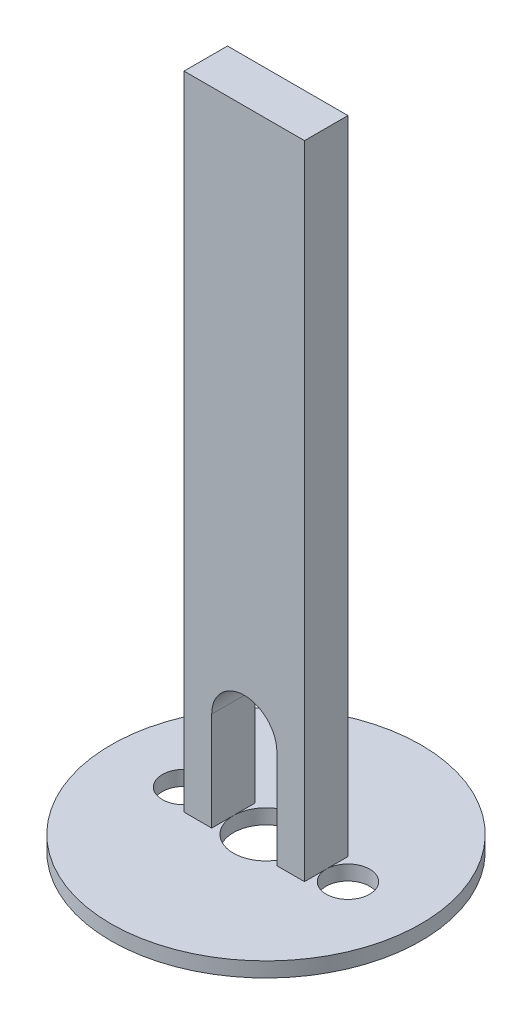
SolidWorks part; units mm, degrees
ref_plane "Front Plane" through (0, 0, 0) normal (0, 0, 1) x (1, 0, 0)
ref_plane "Top Plane" through (0, 0, 0) normal (0, 1, 0) x (1, 0, 0)
ref_plane "Right Plane" through (0, 0, 0) normal (1, 0, 0) x (0, 0, -1)
sketch "Sketch1" plane through (0, 0, 0) normal (0, 1, 0) x (1, 0, 0)
  line L0 (0, 45.1084) -> (0, -45.1084) construction
  line L1 (-87.8036, 0) -> (119.361, 0) construction
  circle A0 centre (0, 0) radius 15.7
  circle A1 centre (0, 0) radius 3.3
  circle A2 centre (-8.3, 0) radius 2.2
  circle A3 centre (8.3, 0) radius 2.2
  point P12 (0, 0)
  dimension "D1" = 31.4
  dimension "D2" = 6.6
  dimension "D3" = 4.4
  dimension "D5" = 4.4
  dimension "D4" = 8.3
  dimension "D6" = 8.3
extrude "Boss-Extrude1" add sketch "Sketch1" along normal blind 1.5
sketch "Sketch2" plane through (0, 1.5, 0) normal (0, 1, 0) x (1, 0, 0)
  line L0 (-23.3183, 0) -> (31.4321, 0) construction
  line L2 (-6.1, -2.2) -> (6.1, -2.2)
  line L3 (-6.1, -2.2) -> (-6.1, 2.2)
  line L4 (-6.1, 2.2) -> (6.1, 2.2)
  line L5 (6.1, -2.2) -> (6.1, 2.2)
  line L6 (-6.1, -2.2) -> (6.1, 2.2) construction
  line L7 (-6.1, 2.2) -> (6.1, -2.2) construction
  point P3 (0, 0)
  dimension "D1" = 12.2
  dimension "D2" = 4.4
extrude "Boss-Extrude2" add sketch "Sketch2" along normal blind 65
sketch "Sketch4" plane through (0, 0, 2.2) normal (0, 0, 1) x (1, 0, 0)
  line L0 (-3.3, 1.5) -> (-3.3, 11.5)
  line L1 (-2.4597, 1.5) -> (2.4597, 1.5) construction
  line L2 (0, 22.6383) -> (0, -2.7885) construction
  line L3 (3.3, 11.5) -> (3.3, 1.5)
  line L4 (15.7, 1.5) -> (-15.7, 1.5) construction
  arc A0 (-3.3, 11.5) -> (3.3, 11.5) centre (0, 11.5) cw
  line M5 (-6.1, 1.5) -> (-2.4597, 1.5)
  line M6 (-2.4597, 1.5) -> (2.4597, 1.5)
  line M7 (2.4597, 1.5) -> (6.1, 1.5)
  dimension "D1" = 3.3
  dimension "D2" = 10
extrude "Cut-Extrude1" cut sketch "Sketch4" against normal blind 90 and the other way through all contours A0 L2 L3 M6 M7 | L2 A0 L0 M5 M6
